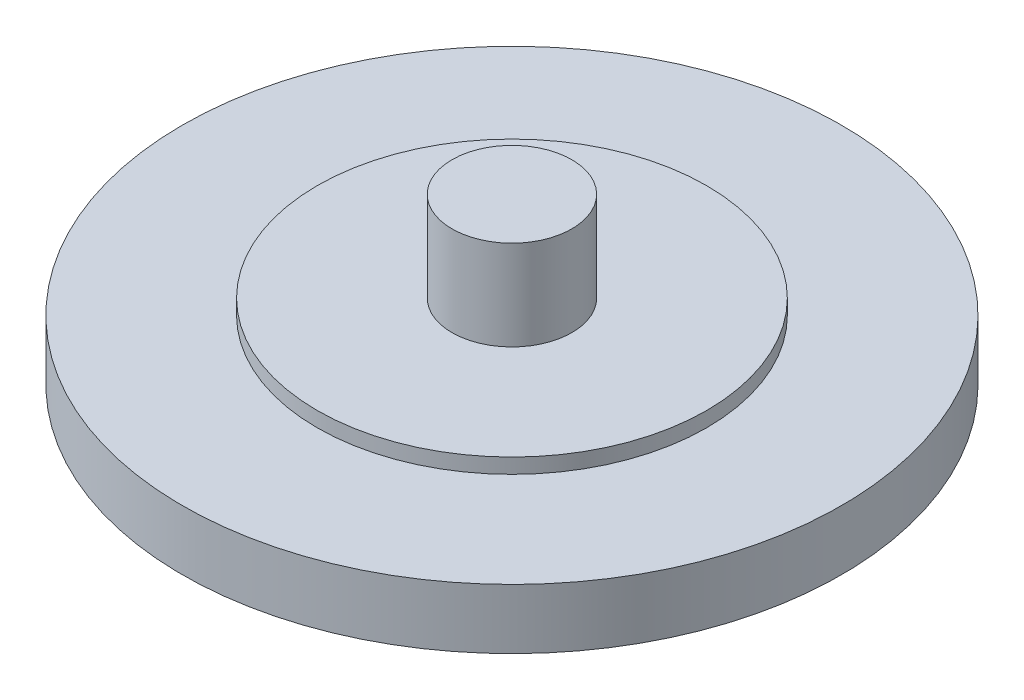
SolidWorks part; units mm, degrees
ref_plane "Front Plane" through (0, 0, 0) normal (0, 0, 1) x (1, 0, 0)
ref_plane "Top Plane" through (0, 0, 0) normal (0, 1, 0) x (1, 0, 0)
ref_plane "Right Plane" through (0, 0, 0) normal (1, 0, 0) x (0, 0, -1)
sketch "Sketch1" plane through (0, 0, 0) normal (0, 0, 1) x (1, 0, 0)
  line L0 (0, 0) -> (11, 0)
  line L1 (11, 0) -> (11, 2)
  line L2 (11, 2) -> (6.5, 2)
  line L3 (6.5, 2) -> (6.5, 2.5)
  line L4 (6.5, 2.5) -> (2, 2.5)
  line L5 (2, 2.5) -> (2, 5.5)
  line L6 (2, 5.5) -> (0, 5.5)
  line L7 (0, 5.5) -> (0, 0) construction
  line L8 (0, 0) -> (0, 5.5)
  dimension "D1" = 11
  dimension "D2" = 2
  dimension "D3" = 0.5
  dimension "D4" = 3
  dimension "D5" = 2
revolve "Revolve1" add sketch "Sketch1" angle 360 about L7
